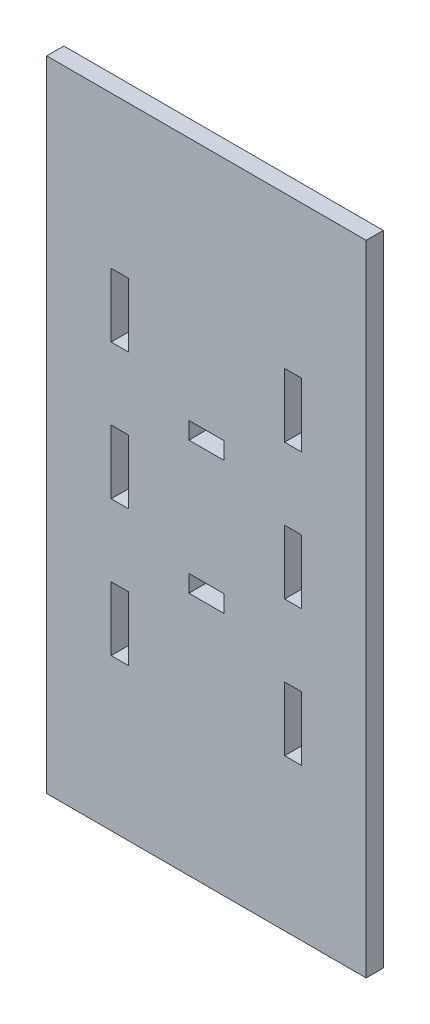
SolidWorks part; units mm, degrees
ref_plane "Front Plane" through (0, 0, 0) normal (0, 0, 1) x (1, 0, 0)
ref_plane "Top Plane" through (0, 0, 0) normal (0, 1, 0) x (1, 0, 0)
ref_plane "Right Plane" through (0, 0, 0) normal (1, 0, 0) x (0, 0, -1)
sketch "Model" plane through (0, 0, 0) normal (0, 0, 1) x (1, 0, 0)
  line L0 (50, 200) -> (50, 0) construction
  line L1 (0, 0) -> (100, 0)
  line L2 (0, 0) -> (0, 200)
  line L3 (0, 200) -> (100, 200)
  line L4 (100, 0) -> (100, 200)
  line L5 (20.17, 152.5) -> (25.52, 152.5)
  line L6 (20.17, 152.5) -> (20.17, 132.5)
  line L7 (20.17, 132.5) -> (25.52, 132.5)
  line L8 (25.52, 152.5) -> (25.52, 132.5)
  line L9 (74.48, 67.5) -> (74.48, 47.5)
  line L10 (20.17, 110) -> (25.52, 110)
  line L11 (20.17, 110) -> (20.17, 90)
  line L12 (20.17, 90) -> (25.52, 90)
  line L13 (25.52, 110) -> (25.52, 90)
  line L14 (20.17, 67.5) -> (25.52, 67.5)
  line L15 (20.17, 67.5) -> (20.17, 47.5)
  line L16 (20.17, 47.5) -> (25.52, 47.5)
  line L17 (25.52, 67.5) -> (25.52, 47.5)
  line L18 (79.83, 47.5) -> (74.48, 47.5)
  line L19 (79.83, 67.5) -> (79.83, 47.5)
  line L56 (79.83, 67.5) -> (74.48, 67.5)
  line L57 (74.48, 110) -> (74.48, 90)
  line L58 (79.83, 90) -> (74.48, 90)
  line L59 (79.83, 110) -> (79.83, 90)
  line L60 (79.83, 110) -> (74.48, 110)
  line L61 (74.48, 152.5) -> (74.48, 132.5)
  line L62 (79.83, 132.5) -> (74.48, 132.5)
  line L63 (79.83, 152.5) -> (79.83, 132.5)
  line L64 (79.83, 152.5) -> (74.48, 152.5)
  line L65 (0, 100) -> (100, 100) construction
  line L66 (44.5, 118.075) -> (55.5, 118.075)
  line L67 (44.5, 118.075) -> (44.5, 123.425)
  line L68 (44.5, 123.425) -> (55.5, 123.425)
  line L69 (55.5, 118.075) -> (55.5, 123.425)
  line L70 (44.5, 118.075) -> (55.5, 123.425) construction
  line L71 (44.5, 123.425) -> (55.5, 118.075) construction
  line L72 (44.5, 76.575) -> (55.5, 81.925) construction
  line L73 (44.5, 81.925) -> (55.5, 76.575) construction
  line L74 (55.5, 81.925) -> (55.5, 76.575)
  line L75 (44.5, 76.575) -> (55.5, 76.575)
  line L76 (44.5, 81.925) -> (44.5, 76.575)
  line L77 (44.5, 81.925) -> (55.5, 81.925)
  point P30 (50, 120.75)
  point P41 (50, 79.25)
  dimension "D3" = 200
  dimension "D4" = 100
  dimension "D5" = 20
  dimension "D6" = 5.35
  dimension "D15" = 47.5
  dimension "D20" = 25.52
  dimension "D23" = 11
  dimension "D24" = 5.35
  dimension "D25" = 76.575
  dimension "D7" = 22.5
  dimension "D8" = 22.5
extrude "Boss-Extrude1" add sketch "Model" along normal blind 5.35
equation "\"mdfthick\"=5.35"
equation "\"D6@Model\"=\"mdfthick\""
equation "\"D24@Model\"=\"mdfthick\""
equation "\"D1@Boss-Extrude1\"=\"mdfthick\""
